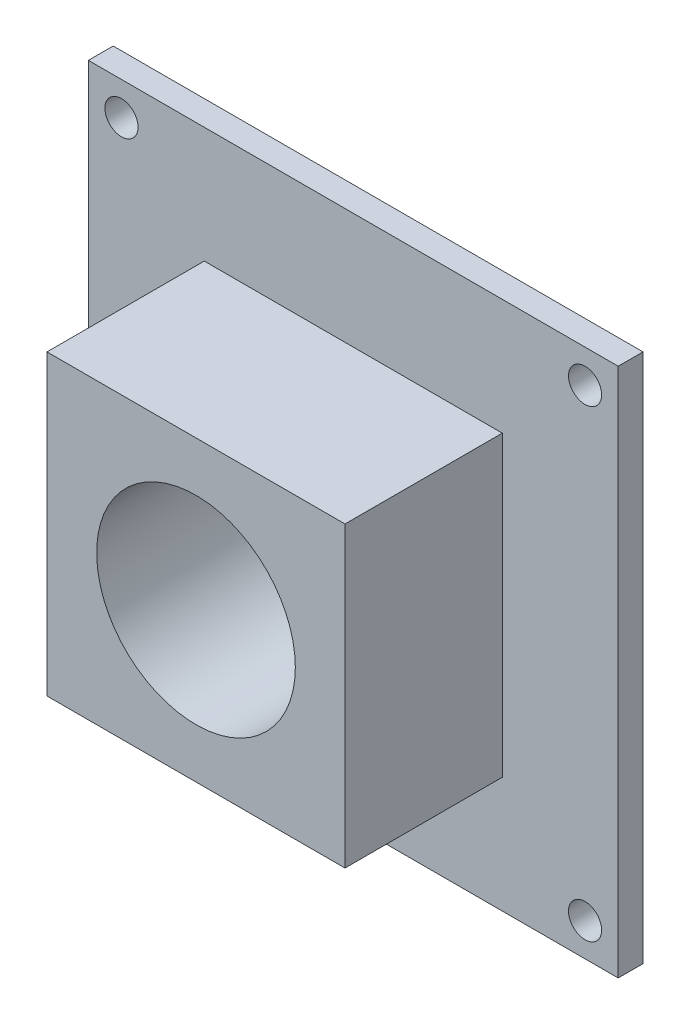
SolidWorks part; units mm, degrees
ref_plane "正面" through (0, 0, 0) normal (0, 0, 1) x (1, 0, 0)
ref_plane "平面" through (0, 0, 0) normal (0, 1, 0) x (1, 0, 0)
ref_plane "右側面" through (0, 0, 0) normal (1, 0, 0) x (0, 0, -1)
sketch "ｽｹｯﾁ1" plane through (0, 0, 0) normal (0, 0, 1) x (1, 0, 0)
  line L1 (16, -16) -> (-16, -16)
  line L2 (16, -16) -> (16, 16)
  line L3 (16, 16) -> (-16, 16)
  line L4 (-16, -16) -> (-16, 16)
  line L5 (16, -16) -> (-16, 16) construction
  line L6 (16, 16) -> (-16, -16) construction
  circle A0 centre (-14, 14) radius 1
  circle A1 centre (14, 14) radius 1
  circle A2 centre (14, -14) radius 1
  circle A3 centre (-14, -14) radius 1
  point P0 (0, 0)
  point P8 (-15.5062, -22.0576)
  point P9 (0, 0)
  point P17 (0, 0)
  dimension "D2" = 2
  dimension "D3" = 2
  dimension "D1" = 32
  dimension "D4" = 4
extrude "ﾎﾞｽ - 押し出し1" add sketch "ｽｹｯﾁ1" along normal blind 1.5
sketch "ｽｹｯﾁ2" plane through (0, 0, 1.5) normal (0, 0, 1) x (1, 0, 0)
  line L1 (9, -9) -> (-9, -9)
  line L2 (9, -9) -> (9, 9)
  line L3 (9, 9) -> (-9, 9)
  line L4 (-9, -9) -> (-9, 9)
  line L5 (9, -9) -> (-9, 9) construction
  line L6 (9, 9) -> (-9, -9) construction
  circle A0 centre (0, 0) radius 6
  point P0 (0, 0)
  dimension "D2" = 12
  dimension "D1" = 18
extrude "ﾎﾞｽ - 押し出し2" add sketch "ｽｹｯﾁ2" along normal blind 9.5
